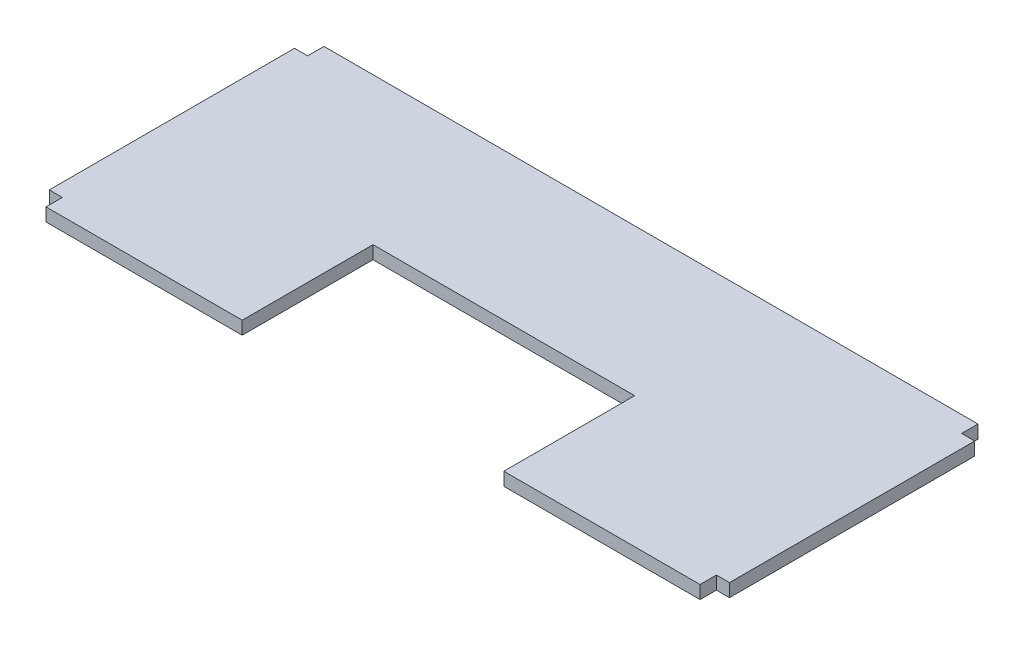
SolidWorks part; units mm, degrees
ref_plane "前视基准面" through (0, 0, 0) normal (0, 0, 1) x (1, 0, 0)
ref_plane "上视基准面" through (0, 0, 0) normal (0, 1, 0) x (1, 0, 0)
ref_plane "右视基准面" through (0, 0, 0) normal (1, 0, 0) x (0, 0, -1)
sketch "草图1" plane through (0, 0, 0) normal (0, 1, 0) x (1, 0, 0)
  line L0 (0, 0) -> (100, 0)
  line L1 (0, 0) -> (0, 42.5)
  line L2 (100, 0) -> (100, 42.5)
  line L3 (0, 42.5) -> (100, 42.5)
  line L4 (-2, 40) -> (0, 40)
  line L5 (-2, 40) -> (-2, 2.5)
  line L6 (0, 40) -> (0, 2.5)
  line L7 (-2, 2.5) -> (0, 2.5)
  line L8 (100, 40) -> (102, 40)
  line L9 (100, 40) -> (100, 2.5)
  line L10 (102, 40) -> (102, 2.5)
  line L11 (100, 2.5) -> (102, 2.5)
  point P0 (0, 40)
  point P3 (0, 2.5)
  point P4 (100, 2.5)
  point P5 (100, 40)
  point P6 (-2, 2.5)
  point P7 (-2, 40)
  point P8 (102, 2.5)
  point P12 (102, 40)
extrude "凸台-拉伸1" add sketch "草图1" along normal blind 2 contours L5 L7 L1 L4 | L3 L1 L0 L2 | L2 L11 L10 L8
sketch "草图2" plane through (0, 2, 0) normal (0, 1, 0) x (1, 0, 0)
  line L0 (30, 0) -> (30, 20)
  line L1 (30, 0) -> (70, 0)
  line L2 (30, 20) -> (70, 20)
  line L3 (70, 0) -> (70, 20)
  line L4 (0, 0) -> (100, 0) construction
  point P4 (0, 0)
  point P5 (0, 0)
extrude "切除-拉伸1" cut sketch "草图2" against normal up to next
